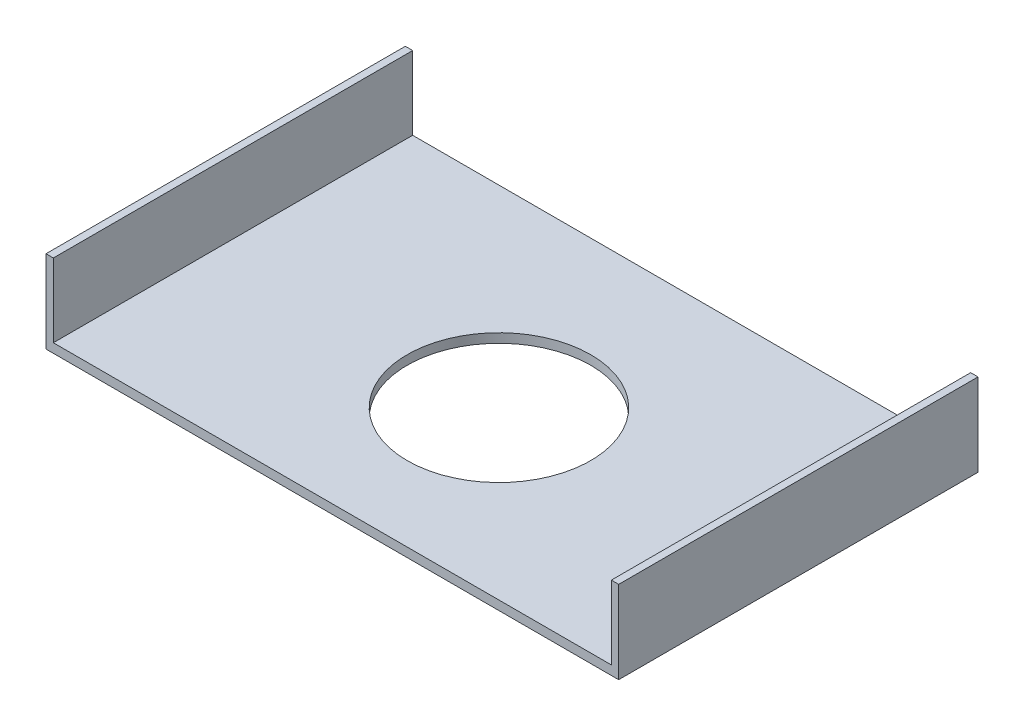
SolidWorks part; units mm, degrees
ref_plane "Front Plane" through (0, 0, 0) normal (0, 0, 1) x (1, 0, 0)
ref_plane "Top Plane" through (0, 0, 0) normal (0, 1, 0) x (1, 0, 0)
ref_plane "Right Plane" through (0, 0, 0) normal (1, 0, 0) x (0, 0, -1)
sketch "Sketch1" plane through (0, 0, 0) normal (0, 1, 0) x (1, 0, 0)
  line L1 (-156, -115) -> (156, -115)
  line L2 (-156, -115) -> (-156, 115)
  line L3 (-156, 115) -> (156, 115)
  line L4 (156, -115) -> (156, 115)
  line L5 (-156, -115) -> (156, 115) construction
  line L6 (-156, 115) -> (156, -115) construction
  point P0 (0, 0)
  dimension "D1" = 312
  dimension "D2" = 230
extrude "Boss-Extrude1" add sketch "Sketch1" along normal blind 5
sketch "Sketch2" plane through (0, 5, 0) normal (0, 1, 0) x (1, 0, 0)
  line L0 (-156, -115) -> (156, -115) construction
  line L1 (-156, 115) -> (-152, 115)
  line L2 (-156, 115) -> (-156, -115)
  line L3 (-156, -115) -> (-152, -115)
  line L4 (-152, 115) -> (-152, -115)
  line L6 (156, 115) -> (152, 115)
  line L7 (156, 115) -> (156, -115)
  line L8 (156, -115) -> (152, -115)
  line L9 (152, 115) -> (152, -115)
  dimension "D1" = 4
  dimension "D2" = 4
extrude "Boss-Extrude2" add sketch "Sketch2" along normal blind 40
sketch "Sketch3" plane through (0, 5, 0) normal (0, 1, 0) x (1, 0, 0)
  circle A0 centre (0, 0) radius 50
  dimension "D1" = 100
extrude "Cut-Extrude1" cut sketch "Sketch3" against normal through all
sketch "Sketch4" plane through (0, 5, 0) normal (0, 1, 0) x (1, 0, 0)
  line L5 (156, -115) -> (156, 115) construction
  line L6 (-156, 115) -> (156, 115)
  line L7 (-156, 115) -> (-156, 105)
  line L8 (-156, 105) -> (156, 105)
  line L9 (156, 115) -> (156, 105)
  dimension "D1" = 10
extrude "Cut-Extrude2" cut sketch "Sketch4" against normal through all and the other way through all
sketch "Sketch5" plane through (156, 0, 0) normal (1, 0, 0) x (0, 0, -1)
  line L0 (-90.7655, 93) -> (-90.7655, -507) construction
  line L1 (-115, 0) -> (-90.7655, 0)
  line L2 (-115, 0) -> (-115, 45)
  line L3 (-115, 45) -> (-90.7655, 45)
  line L4 (-90.7655, 0) -> (-90.7655, 45)
  line L5 (-115, 45) -> (105, 45) construction
extrude "Cut-Extrude3" cut sketch "Sketch5" against normal through all
